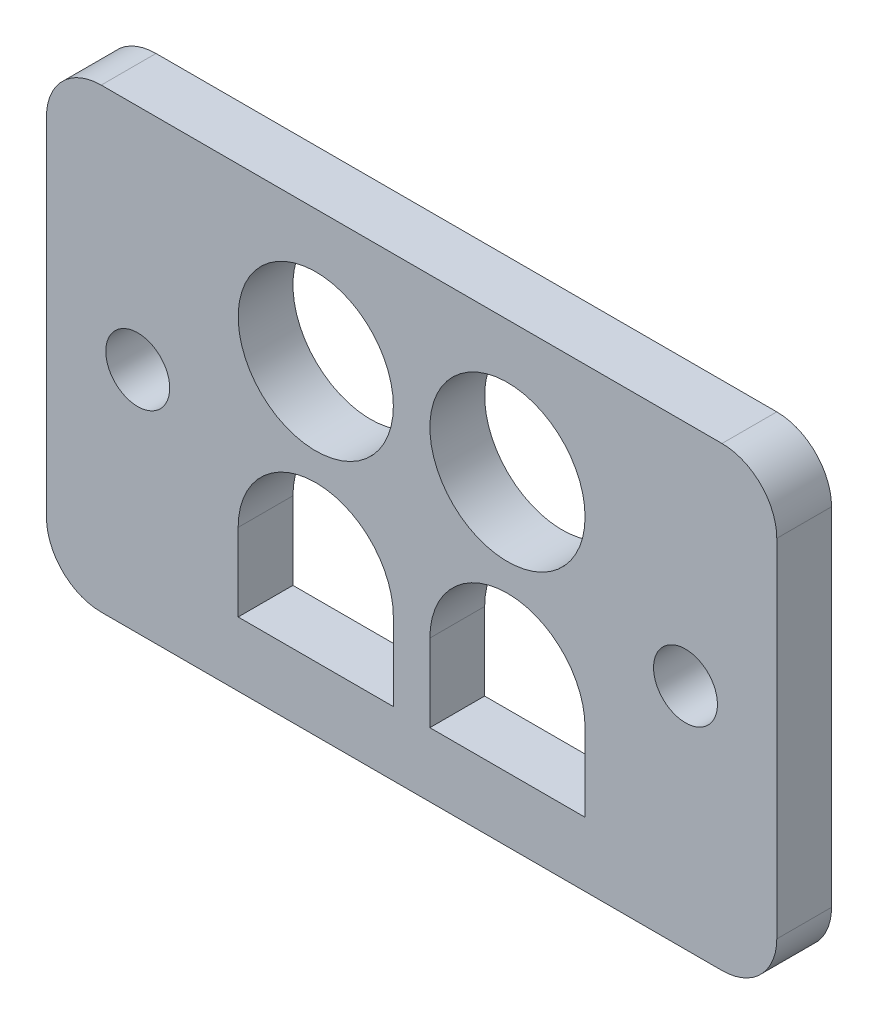
SolidWorks part; units mm, degrees
ref_plane "Front Plane" through (0, 0, 0) normal (0, 0, 1) x (1, 0, 0)
ref_plane "Top Plane" through (0, 0, 0) normal (0, 1, 0) x (1, 0, 0)
ref_plane "Right Plane" through (0, 0, 0) normal (1, 0, 0) x (0, 0, -1)
sketch "Sketch1" plane through (0, 0, 0) normal (0, 0, 1) x (1, 0, 0)
  line L1 (-17, 12.5) -> (17, 12.5)
  line L2 (-20, 9.5) -> (-20, -9.5)
  line L3 (-17, -12.5) -> (17, -12.5)
  line L4 (20, 9.5) -> (20, -9.5)
  line L5 (-20, 12.5) -> (20, -12.5) construction
  line L6 (-20, -12.5) -> (20, 12.5) construction
  arc A0 (-20, -9.5) -> (-17, -12.5) centre (-17, -9.5) ccw
  arc A1 (17, -12.5) -> (20, -9.5) centre (17, -9.5) ccw
  arc A2 (17, 12.5) -> (20, 9.5) centre (17, 9.5) cw
  arc A3 (-17, 12.5) -> (-20, 9.5) centre (-17, 9.5) ccw
  point P0 (0, 0)
  dimension "D3" = 3
  dimension "D1" = 25
  dimension "D2" = 40
extrude "Boss-Extrude1" add sketch "Sketch1" along normal blind 3
sketch "Sketch2" plane through (0, 0, 3) normal (0, 0, 1) x (1, 0, 0)
  line L2 (-9.5, -4.73) -> (-9.5, -8.98)
  line L3 (-9.5, -8.98) -> (-1, -8.98)
  line L4 (-1, -4.73) -> (-1, -8.98)
  line L8 (1, -4.73) -> (1, -8.98)
  line L9 (1, -8.98) -> (9.5, -8.98)
  line L10 (9.5, -4.73) -> (9.5, -8.98)
  line L13 (17, 12.5) -> (-17, 12.5) construction
  line L14 (20, -9.5) -> (20, 9.5) construction
  circle A0 centre (-5.25, 5.27) radius 4.25
  circle A1 centre (5.25, 5.27) radius 4.25
  arc A3 (9.5, -4.73) -> (1, -4.73) centre (5.25, -4.73) ccw
  arc A4 (-1, -4.73) -> (-9.5, -4.73) centre (-5.25, -4.73) ccw
  point P4 (-5.25, -4.73)
  point P9 (5.25, -4.73)
  dimension "D1" = 8.5
  dimension "D2" = 8.5
  dimension "D3" = 8.5
  dimension "D4" = 8.5
  dimension "D5" = 0
  dimension "D6" = 0
  dimension "D9" = 10
  dimension "D10" = 10
  dimension "D11" = 2
  dimension "D12" = 0
  dimension "D13" = 7.23
  dimension "D14" = 14.75
extrude "Cut-Extrude1" cut sketch "Sketch2" against normal blind 3
sketch "Sketch3" plane through (0, 0, 3) normal (0, 0, 1) x (1, 0, 0)
  line L0 (-20, 9.5) -> (-20, -9.5) construction
  line L1 (20, -9.5) -> (20, 9.5) construction
  circle A0 centre (-15, 0) radius 1.75
  circle A1 centre (15, 0) radius 1.75
  dimension "D1" = 3.5
  dimension "D2" = 3.5
  dimension "D3" = 5
  dimension "D4" = 5
extrude "Cut-Extrude2" cut sketch "Sketch3" against normal blind 3
